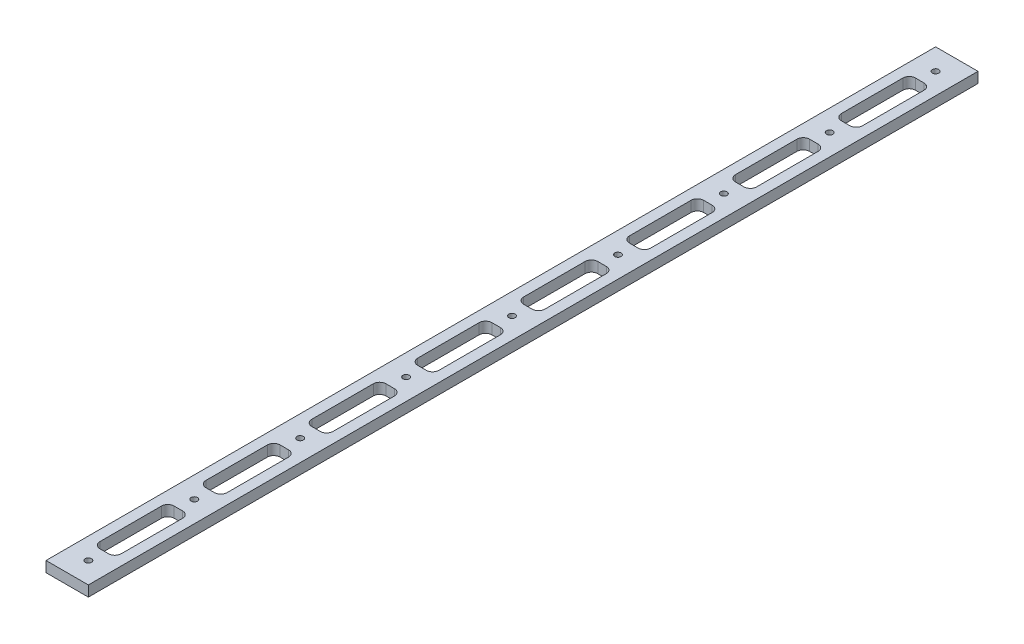
SolidWorks part; units mm, degrees
material "Thornel Mat VMA"
ref_plane "前视基准面" through (0, 0, 0) normal (0, 0, 1) x (1, 0, 0)
ref_plane "上视基准面" through (0, 0, 0) normal (0, 1, 0) x (1, 0, 0)
ref_plane "右视基准面" through (0, 0, 0) normal (1, 0, 0) x (0, 0, -1)
sketch "草图1" plane through (0, 0, 0) normal (0, 1, 0) x (1, 0, 0)
  line L1 (-10, -210) -> (10, -210)
  line L2 (-10, -210) -> (-10, 210)
  line L3 (-10, 210) -> (10, 210)
  line L4 (10, -210) -> (10, 210)
  line L5 (-10, -210) -> (10, 210) construction
  line L6 (-10, 210) -> (10, -210) construction
  point P0 (0, 0)
  dimension "D1" = 20
  dimension "D2" = 420
extrude "凸台-拉伸1" add sketch "草图1" along normal blind 5
sketch "草图2" plane through (0, 5, 0) normal (0, 1, 0) x (1, 0, 0)
  line L0 (0, 210) -> (0, -210) construction
  line L1 (10, 210) -> (-10, 210) construction
  line L2 (-10, -210) -> (10, -210) construction
  line L3 (-10, 0) -> (10, 0) construction
  line L4 (-10, 210) -> (-10, -210) construction
  line L5 (10, -210) -> (10, 210) construction
  circle A0 centre (0, 0) radius 1.5
  circle A1 centre (0, 50) radius 1.5
  circle A2 centre (0, 100) radius 1.5
  circle A3 centre (0, 150) radius 1.5
  circle A4 centre (0, 200) radius 1.5
  circle A5 centre (0, -200) radius 1.5
  circle A6 centre (0, -150) radius 1.5
  circle A7 centre (0, -100) radius 1.5
  circle A8 centre (0, -50) radius 1.5
  dimension "D1" = 3
  dimension "D2" = 5
extrude "切除-拉伸1" cut sketch "草图2" against normal through all
sketch "草图3" plane through (0, 5, 0) normal (0, 1, 0) x (1, 0, 0)
  line L0 (0, 200) -> (0, 150) construction
  line L1 (-5, 107.5) -> (-5, 142.5)
  line L2 (-5, 157.5) -> (5, 157.5)
  line L3 (-5, 157.5) -> (-5, 192.5)
  line L4 (-5, 192.5) -> (5, 192.5)
  line L5 (5, 157.5) -> (5, 192.5)
  line L6 (-5, 157.5) -> (5, 192.5) construction
  line L7 (-5, 192.5) -> (5, 157.5) construction
  line L8 (-5, 107.5) -> (5, 107.5)
  line L9 (5, 107.5) -> (5, 142.5)
  line L10 (-5, 142.5) -> (5, 142.5)
  line L11 (-5, 57.5) -> (-5, 92.5)
  line L12 (-5, 57.5) -> (5, 57.5)
  line L13 (5, 57.5) -> (5, 92.5)
  line L14 (-5, 92.5) -> (5, 92.5)
  line L15 (-5, 7.5) -> (-5, 42.5)
  line L16 (-5, 7.5) -> (5, 7.5)
  line L17 (5, 7.5) -> (5, 42.5)
  line L18 (-5, 42.5) -> (5, 42.5)
  line L19 (-5, -42.5) -> (-5, -7.5)
  line L20 (-5, -42.5) -> (5, -42.5)
  line L21 (5, -42.5) -> (5, -7.5)
  line L22 (-5, -7.5) -> (5, -7.5)
  line L23 (-5, -92.5) -> (-5, -57.5)
  line L24 (-5, -92.5) -> (5, -92.5)
  line L25 (5, -92.5) -> (5, -57.5)
  line L26 (-5, -57.5) -> (5, -57.5)
  line L27 (-5, -142.5) -> (-5, -107.5)
  line L28 (-5, -142.5) -> (5, -142.5)
  line L29 (5, -142.5) -> (5, -107.5)
  line L30 (-5, -107.5) -> (5, -107.5)
  line L31 (-5, -192.5) -> (-5, -157.5)
  line L32 (-5, -192.5) -> (5, -192.5)
  line L33 (5, -192.5) -> (5, -157.5)
  line L34 (-5, -157.5) -> (5, -157.5)
  point P4 (0, 175)
  dimension "D1" = 35
  dimension "D2" = 10
extrude "切除-拉伸2" cut sketch "草图3" against normal through all
fillet "圆角1" radius 3 32 edges at (5, 2.5, 157.5) (-5, 2.5, 157.5) (-5, 2.5, 192.5) (5, 2.5, 192.5) (-5, 2.5, 142.5) (5, 2.5, 142.5) (-5, 2.5, 107.5) (5, 2.5, 107.5) (-5, 2.5, 92.5) (5, 2.5, 92.5) (-5, 2.5, 57.5) (5, 2.5, 57.5) (-5, 2.5, 42.5) (5, 2.5, 42.5) (-5, 2.5, 7.5) (5, 2.5, 7.5) (-5, 2.5, -7.5) (5, 2.5, -7.5) (-5, 2.5, -42.5) (5, 2.5, -42.5) (-5, 2.5, -57.5) (5, 2.5, -57.5) (5, 2.5, -92.5) (-5, 2.5, -92.5) (-5, 2.5, -107.5) (5, 2.5, -107.5) (5, 2.5, -142.5) (-5, 2.5, -142.5) (-5, 2.5, -157.5) (5, 2.5, -157.5) (5, 2.5, -192.5) (-5, 2.5, -192.5)
